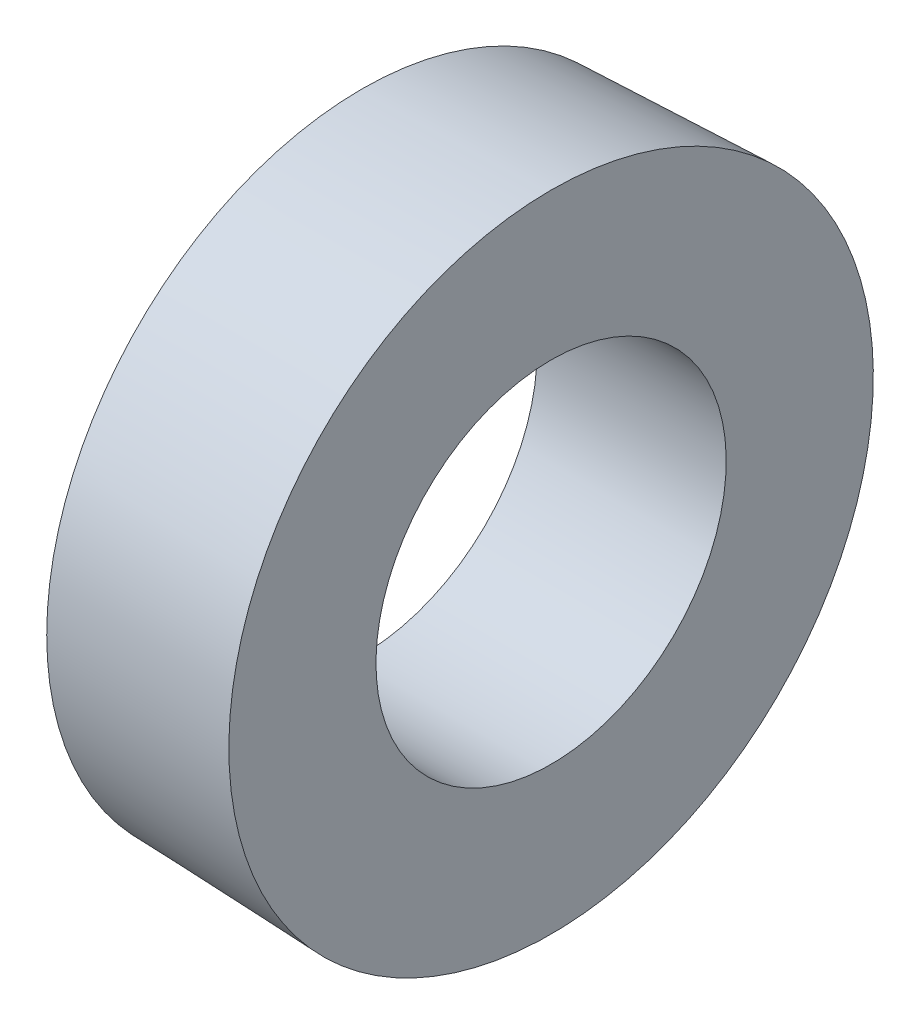
SolidWorks part; units mm, degrees
ref_plane "Front Plane" through (0, 0, 0) normal (0, 0, 1) x (1, 0, 0)
ref_plane "Top Plane" through (0, 0, 0) normal (0, 1, 0) x (1, 0, 0)
ref_plane "Right Plane" through (0, 0, 0) normal (1, 0, 0) x (0, 0, -1)
sketch "Sketch1" plane through (0, 0, 0) normal (0, 0, 1) x (1, 0, 0)
  line L0 (0, 0) -> (5500, 0) construction
  line L1 (4480, 250) -> (4480, 450)
  line L2 (4480, 450) -> (4750, 460)
  line L3 (4750, 460) -> (4750, 250)
  line L4 (4750, 250) -> (4480, 250)
revolve "Revolve1" add sketch "Sketch1" angle 360 about L0
